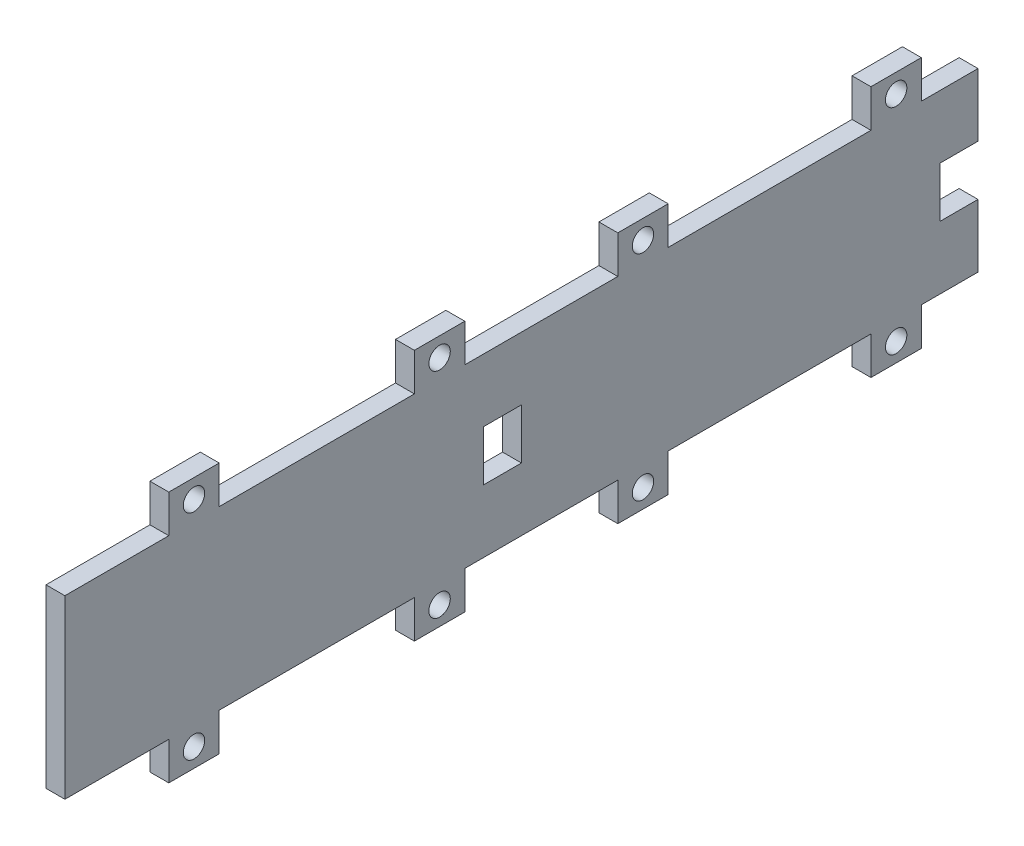
SolidWorks part; units mm, degrees
ref_plane "Front Plane" through (0, 0, 0) normal (0, 0, 1) x (1, 0, 0)
ref_plane "Top Plane" through (0, 0, 0) normal (0, 1, 0) x (1, 0, 0)
ref_plane "Right Plane" through (0, 0, 0) normal (1, 0, 0) x (0, 0, -1)
sketch "草圖1" plane through (0, 0, 0) normal (1, 0, 0) x (0, 0, -1)
  line L0 (-10.5, 14) -> (-19.5, 14)
  line L1 (-19.5, 14) -> (-19.5, 20)
  line L2 (-19.5, 20) -> (-27.5, 20)
  line L3 (-27.5, 20) -> (-27.5, 14)
  line L4 (-27.5, 14) -> (-59.7, 14)
  line L5 (-59.7, 14) -> (-59.7, 20)
  line L6 (-59.7, 20) -> (-67.7, 20)
  line L7 (-67.7, 20) -> (-67.7, 14)
  line L8 (-67.7, 14) -> (-92, 14)
  line L9 (-92, 14) -> (-92, 20)
  line L10 (-92, 20) -> (-100, 20)
  line L11 (-100, 20) -> (-100, 14)
  line L12 (-100, 14) -> (-131, 14)
  line L13 (-131, 14) -> (-131, 20)
  line L14 (-131, 20) -> (-139, 20)
  line L15 (-139, 20) -> (-139, 14)
  line L16 (-139, 14) -> (-155.5, 14)
  line L17 (-155.5, 14) -> (-155.5, -14)
  line L18 (-155.5, -14) -> (-139, -14)
  line L19 (-139, -14) -> (-139, -20)
  line L20 (-139, -20) -> (-131, -20)
  line L21 (-131, -20) -> (-131, -14)
  line L22 (-131, -14) -> (-100, -14)
  line L23 (-100, -14) -> (-100, -20)
  line L24 (-100, -20) -> (-92, -20)
  line L25 (-92, -20) -> (-92, -14)
  line L26 (-92, -14) -> (-67.7, -14)
  line L27 (-67.7, -14) -> (-67.7, -20)
  line L28 (-67.7, -20) -> (-59.7, -20)
  line L29 (-59.7, -20) -> (-59.7, -14)
  line L30 (-59.7, -14) -> (-27.5, -14)
  line L31 (-27.5, -14) -> (-27.5, -20)
  line L32 (-27.5, -20) -> (-19.5, -20)
  line L33 (-19.5, -20) -> (-19.5, -14)
  line L34 (-19.5, -14) -> (-10.5, -14)
  line L35 (-10.5, -14) -> (-10.5, -4)
  line L36 (-10.5, -4) -> (-16.5, -4)
  line L37 (-16.5, -4) -> (-16.5, 4)
  line L38 (-16.5, 4) -> (-10.5, 4)
  line L39 (-10.5, 4) -> (-10.5, 14)
  line L40 (-89, -4) -> (-83, -4)
  line L41 (-83, -4) -> (-83, 4)
  line L42 (-83, 4) -> (-89, 4)
  line L43 (-89, 4) -> (-89, -4)
  circle A0 centre (-23.5, 17) radius 1.7
  circle A1 centre (-23.5, -17) radius 1.7
  circle A2 centre (-63.7, 17) radius 1.7
  circle A3 centre (-63.7, -17) radius 1.7
  circle A4 centre (-96, 17) radius 1.7
  circle A5 centre (-96, -17) radius 1.7
  circle A6 centre (-135, 17) radius 1.7
  circle A7 centre (-135, -17) radius 1.7
extrude "填料-伸長1" add sketch "草圖1" along normal blind 3 from offset 20.5
